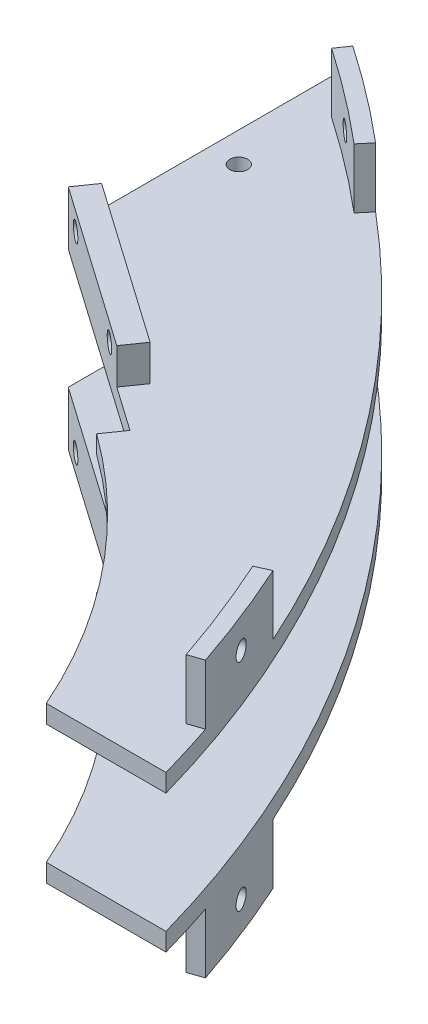
SolidWorks part; units mm, degrees
ref_plane "Front Plane" through (0, 0, 0) normal (0, 0, 1) x (1, 0, 0)
ref_plane "Top Plane" through (0, 0, 0) normal (0, 1, 0) x (1, 0, 0)
ref_plane "Right Plane" through (0, 0, 0) normal (1, 0, 0) x (0, 0, -1)
sketch "Sketch1" plane through (0, 0, 0) normal (0, 1, 0) x (1, 0, 0)
  line L0 (0, 0) -> (20, 0)
  line L1 (-67.91, 116.18) -> (-67.91, 72.58)
  arc A0 (0, 0) -> (-67.91, 72.58) centre (-137.2997, -60.4052) ccw
  arc A1 (20, 0) -> (-67.91, 116.18) centre (-172.4876, -54.3003) ccw
  dimension "D1" = 150
  dimension "D5" = 200
  dimension "D2" = 67.91
  dimension "D3" = 20
  dimension "D4" = 43.6
  dimension "D6" = 72.58
extrude "Boss-Extrude1" add sketch "Sketch1" along normal blind 3
sketch "Sketch2" plane through (0, 0, 0) normal (0, -1, 0) x (1, 0, 0)
  line L0 (-66.91, -72.0534) -> (-66.91, -70.5834) construction
  line L1 (-66.91, -70.5834) -> (-32.5056, -46.4932)
  line L2 (-67.91, -116.18) -> (-67.91, -72.58) construction
  line L3 (-66.91, -70.5834) -> (-67.91, -71.2836)
  line L4 (-67.91, -71.2836) -> (-67.91, -76.1667)
  line L5 (-32.5056, -51.3763) -> (-32.5056, -46.4932)
  line L6 (-67.91, -76.1667) -> (-32.5056, -51.3763)
  arc A0 (-67.91, -72.58) -> (0, 0) centre (-137.2997, 60.4052) ccw construction
  dimension "D5" = 4
  dimension "D1" = 1.47
  dimension "D2" = 1
  dimension "D3" = 125
  dimension "D4" = 42
extrude "Boss-Extrude2" add sketch "Sketch2" along normal blind 6
sketch "Sketch3" plane through (13.4449, 0, -19.2014) normal (0.5736, 0, -0.8192) x (-0.8192, 0, -0.5736)
  line L0 (122.2667, 3) -> (-16.383, 3) construction
  line L1 (99.3161, -6) -> (99.3161, 0) construction
  line L2 (53.2944, -6) -> (62.2961, -6)
  line L3 (99.3161, -6) -> (56.0953, -6) construction
  line L4 (62.2961, -6) -> (62.2961, 0)
  line L5 (-16.383, 0) -> (122.2667, 0) construction
  line L6 (62.2961, 0) -> (53.2944, 0)
  line L7 (53.2944, 0) -> (53.2944, -6)
  line L8 (99.3161, -6) -> (99.3161, 0)
  line L9 (99.3161, 0) -> (95.2961, 0)
  line L10 (95.2961, 0) -> (95.2961, -6)
  line L11 (95.2961, -6) -> (99.3161, -6)
  circle A0 centre (90.2961, -3) radius 1.5
  circle A1 centre (67.2961, -3) radius 1.5
  dimension "D1" = 6
  dimension "D3" = 3
  dimension "D2" = 9.02
  dimension "D4" = 23
  dimension "D5" = 5
  dimension "D6" = 5
extrude "Cut-Extrude1" cut sketch "Sketch3" against normal through all
sketch "Sketch5" plane through (0, 0, 0) normal (0, 1, 0) x (1, 0, 0)
  line L0 (-66.9113, 70.5843) -> (-67.91, 70.5843)
  line L1 (-67.91, 70.5843) -> (-67.91, 72.58)
  line L2 (-66.9113, 70.5843) -> (-32.5056, 46.4932)
  line L3 (-32.5056, 46.4932) -> (-34.7999, 43.2166)
  arc A1 (0, 0) -> (-67.91, 72.58) centre (-137.2997, -60.4052) ccw
  arc A2 (0, 0) -> (-67.91, 72.58) centre (-137.2997, -60.4052) ccw construction
  arc A3 (-34.7999, 43.2166) -> (0, 0) centre (-97.5095, -42.8995) cw
  dimension "D1" = 4
extrude "Boss-Extrude3" add sketch "Sketch5" along normal up to surface (3 mm away) up to face at (-24.6695, 3, -50.7095)
sketch "Sketch6" plane through (0, 0, 0) normal (0, -1, 0) x (1, 0, 0)
  line L0 (0, 0) -> (20, 0) construction
  line L1 (-67.91, -116.18) -> (-67.91, -70.5843) construction
  line L2 (17.3481, 0) -> (20, 0)
  line L3 (-67.91, -113.18) -> (-67.91, -116.18)
  line L4 (-60.9603, -108.6346) -> (-59.5194, -110.7397)
  line L5 (14.6278, -8.7391) -> (17.0452, -9.5535)
  line L6 (7.3961, -27.112) -> (9.7202, -28.1638)
  line L7 (-43.6009, -98.6318) -> (-45.2448, -96.6811)
  arc A0 (-67.91, -116.18) -> (20, 0) centre (-172.4876, 54.3003) ccw
  arc A1 (17.3481, 0) -> (-67.91, -113.18) centre (-172.4876, 54.3003) cw
  arc A2 (-67.91, -116.18) -> (20, 0) centre (-172.4876, 54.3003) ccw construction
  arc M11 (-67.91, -116.18) -> (20, 0) centre (-172.4876, 54.3003) ccw
  dimension "D1" = 3
  dimension "D2" = 10
  dimension "D3" = 10
  dimension "D4" = 20
  dimension "D5" = 20
extrude "Boss-Extrude4" add sketch "Sketch6" along normal blind 10 contours L7 A1 L4 M11 | L5 A1 L6 M11
sketch "Sketch7" plane through (0, -10, 0) normal (0, -1, 0) x (1, 0, 0)
  line L0 (-51.4087, -104.8848) -> (-172.4876, 54.3003) construction
  line L1 (-172.4876, 54.3003) -> (13.6155, -18.9503) construction
  arc A2 (9.7202, -28.1638) -> (17.0452, -9.5535) centre (-172.4876, 54.3003) ccw construction
  arc A3 (-59.5194, -110.7397) -> (-43.6009, -98.6318) centre (-172.4876, 54.3003) ccw construction
ref_plane "Plane1" through (-51.4087, -10, -104.8848) normal (0.6054, 0, -0.7959) x (-0.7959, 0, -0.6054)
sketch "Sketch8" plane through (-51.4087, -10, -104.8848) normal (0.6054, 0, -0.7959) x (-0.7959, 0, -0.6054)
  line L0 (10, 10) -> (-10, 0) construction
  circle A0 centre (0, 5) radius 1.5
  dimension "D1" = 3
extrude "Cut-Extrude2" cut sketch "Sketch8" against normal through all
ref_plane "Plane2" through (18.2474, 0, -7.1822) normal (0.9305, 0, -0.3663) x (-0.3663, 0, -0.9305)
sketch "Sketch9" plane through (18.2474, 0, -7.1822) normal (0.9305, 0, -0.3663) x (-0.3663, 0, -0.9305)
  line L0 (2.6468, 0) -> (22.6468, -10) construction
  line L1 (116.4255, -10) -> (12.6468, -10) construction
  line L2 (22.6468, -10) -> (22.6468, 0) construction
  circle A0 centre (12.6468, -5) radius 1.5
  dimension "D1" = 3
extrude "Cut-Extrude3" cut sketch "Sketch9" against normal through all
sketch "Sketch11" plane through (0, 0, 0) normal (0, -1, 0) x (1, 0, 0)
  line L0 (-66.91, -70.5834) -> (-66.91, -115.5625)
  line L1 (-66.91, -115.5625) -> (-66.91, -117.7489)
  line L2 (-66.91, -117.7489) -> (-78.6262, -99.1021)
  line L3 (-66.91, -70.5834) -> (-69.5392, -68.4269)
  line L4 (-69.5392, -68.4269) -> (-72.5136, -88.0424)
  arc A0 (-67.91, -116.18) -> (-59.5194, -110.7397) centre (-172.4876, 54.3003) ccw construction
  arc A1 (-78.6262, -99.1021) -> (-72.5136, -88.0424) centre (-72.5136, -95.2615) cw
extrude "Cut-Extrude5" cut sketch "Sketch11" against normal through all
sketch "Sketch10" plane through (0, 0, 0) normal (0, -1, 0) x (1, 0, 0)
  line L0 (-66.91, -93.0744) -> (-61.91, -94.0744) construction
  line L2 (-66.91, -115.5625) -> (-66.91, -70.5862) construction
  circle A0 centre (-61.91, -94.0744) radius 1.5
  dimension "D1" = 5
  dimension "3" = 3
  dimension "D2" = 1
extrude "Cut-Extrude4" cut sketch "Sketch10" against normal through all
ref_plane "Plane3" through (0, 13, 0) normal (0, 1, 0) x (1, 0, 0)
mirror "Mirror2" about plane through (0, 13, 0) normal (0, 1, 0) of bodies 108
